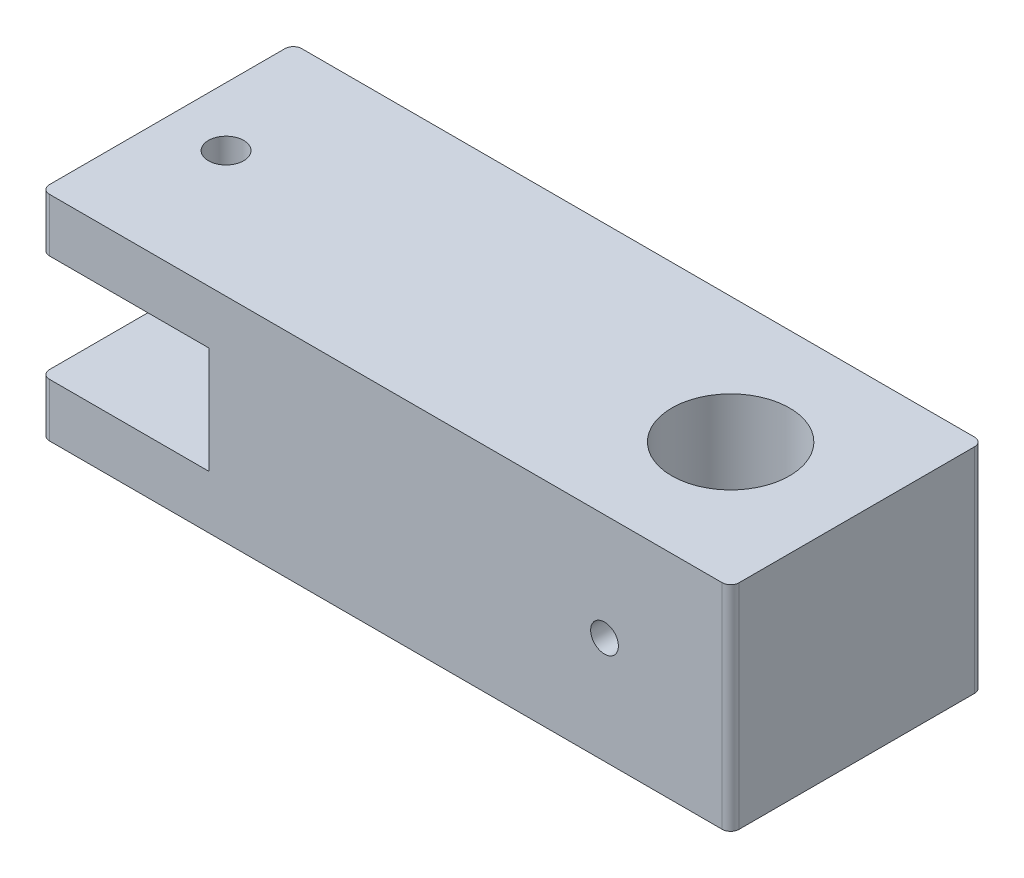
SolidWorks part; units mm, degrees
material "6061 Alloy"
ref_plane "Front Plane" through (0, 0, 0) normal (0, 0, 1) x (1, 0, 0)
ref_plane "Top Plane" through (0, 0, 0) normal (0, 1, 0) x (1, 0, 0)
ref_plane "Right Plane" through (0, 0, 0) normal (1, 0, 0) x (0, 0, -1)
sketch "Sketch1" plane through (0, 0, 0) normal (0, 1, 0) x (1, 0, 0)
  line L0 (-67, -15) -> (15, -15)
  line L1 (-67, 15) -> (15, 15)
  line L9 (15, 15) -> (15, -15)
  line L10 (-67, 15) -> (-67, -15)
  line L11 (-60, 0) -> (0, 0) construction
  circle A0 centre (0, 0) radius 7
  circle A1 centre (-60, 0) radius 2.1
  point P10 (15, 0)
  dimension "D1" = 14
  dimension "D2" = 4.2
  dimension "D3" = 60
  dimension "D4" = 15
  dimension "D6" = 7
  dimension "D5" = 30
extrude "Boss-Extrude1" add sketch "Sketch1" against normal blind 25.4 contours L1 L9 L0 L10
sketch "Sketch2" plane through (0, 0, 15) normal (0, 0, -1) x (-1, 0, 0)
  line L0 (67, -25.4) -> (67, 0) construction
  line L1 (47, -6.35) -> (67, -6.35)
  line L2 (47, -6.35) -> (47, -19.05)
  line L3 (47, -19.05) -> (67, -19.05)
  line L4 (67, -6.35) -> (67, -19.05)
  line L5 (0, 0) -> (0, -25.4) construction
  line L6 (-15, -25.4) -> (67, -25.4) construction
  circle A0 centre (0, -12.7) radius 2 construction
  point P4 (67, -12.7)
  point P5 (0, -12.7)
  dimension "D3" = 4
  dimension "D1" = 12.7
  dimension "D2" = 20
extrude "Cut-Extrude1" cut sketch "Sketch2" along normal blind 32 contours L4 L3 L2 L1
fillet "Fillet1" radius 1 6 edges at (-67, -3.175, 15) (-67, -3.175, -15) (-67, -22.225, -15) (15, -12.7, -15) (15, -12.7, 15) (-67, -22.225, 15)
hole_wizard "Tap Drill for M4x0.7 Tap1" positions "3DSketch1" profile "Sketch3" hole size "M4x0.7" standard "ANSI Metric" end condition through all
sketch3d "3DSketch1"
  point P0 (0, -12.7, 15)
sketch "Sketch3" plane through (0, -12.7, 15) normal (1, 0, 0) x (0, -1, 0)
  line L0 (0, 0) -> (0, 30)
  line L1 (0, 30) -> (1.65, 30)
  line L2 (1.65, 30) -> (1.65, 0)
  line L5 (1.65, 0) -> (0, 0)
  line L11 (0, -6.35) -> (0, 107.95) construction
  dimension "Thru Hole Dia." = 3.3
  dimension "Thru Hole Depth" = 30
